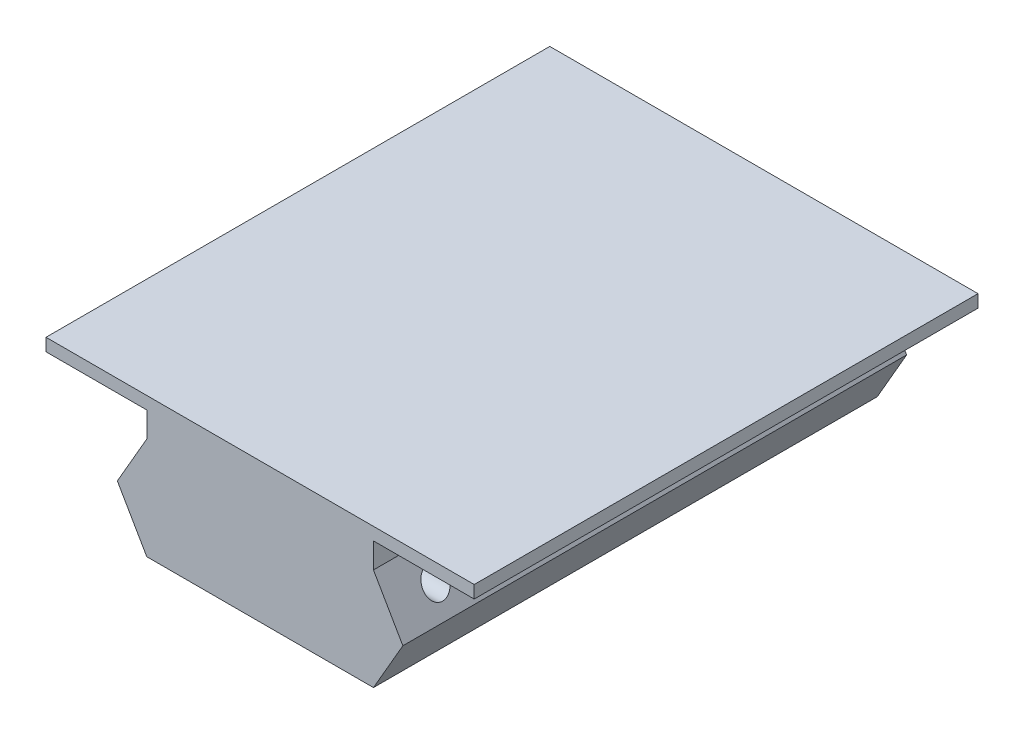
SolidWorks part; units mm, degrees
ref_plane "Front Plane" through (0, 0, 0) normal (0, 0, 1) x (1, 0, 0)
ref_plane "Top Plane" through (0, 0, 0) normal (0, 1, 0) x (1, 0, 0)
ref_plane "Right Plane" through (0, 0, 0) normal (1, 0, 0) x (0, 0, -1)
sketch "Sketch1" plane through (0, 0, 0) normal (0, 0, 1) x (1, 0, 0)
  line L0 (0, 0) -> (9.693, 0) construction
  line L1 (9.693, 0) -> (-8.307, 0)
  line L2 (-8.307, 0) -> (-10.642, 4.0443)
  line L3 (-10.642, 4.0443) -> (-8.307, 8.0887)
  line L5 (9.693, 8.0887) -> (12.028, 4.0443)
  line L6 (12.028, 4.0443) -> (9.693, 0)
  line L7 (-8.307, 8.0887) -> (-8.307, 10.0887)
  line L8 (-8.307, 10.0887) -> (-16.307, 10.0887)
  line L9 (-16.307, 10.0887) -> (-16.307, 11.0887)
  line L10 (-16.307, 11.0887) -> (17.693, 11.0887)
  line L11 (17.693, 11.0887) -> (17.693, 10.0887)
  line L12 (17.693, 10.0887) -> (9.693, 10.0887)
  line L13 (9.693, 10.0887) -> (9.693, 8.0887)
  dimension "D1" = 18
  dimension "D2" = 120
  dimension "D3" = 120
  dimension "D4" = 120
  dimension "D5" = 120
  dimension "D6" = 4.67
  dimension "D7" = 34
  dimension "D8" = 2
  dimension "D9" = 8
extrude "Boss-Extrude1" add sketch "Sketch1" against normal blind 40 contours L10 L11 L12 L13 L5 L6 L1 L2 L3 L7 L8 L9
sketch "Sketch2" plane through (0, 0, 0) normal (1, 0, 0) x (0, 0, -1)
  line L0 (40, 8.0887) -> (0, 8.0887) construction
  line L1 (0, 55) -> (0, -55) construction
  circle A0 centre (3.71, 5.9887) radius 1
  dimension "D1" = 2
  dimension "D2" = 2.1
  dimension "D3" = 3.71
extrude "Cut-Extrude1" cut sketch "Sketch2" against normal through all both and the other way through all
sketch "Sketch3" plane through (0, 0, 0) normal (1, 0, 0) x (0, 0, -1)
  line L0 (-5.5306, 10.7632) -> (49994.4694, 10.7632) construction
pattern_linear "LPattern1" count 10 spacing 3.71 along (0, 0, -1) of "Cut-Extrude1"
